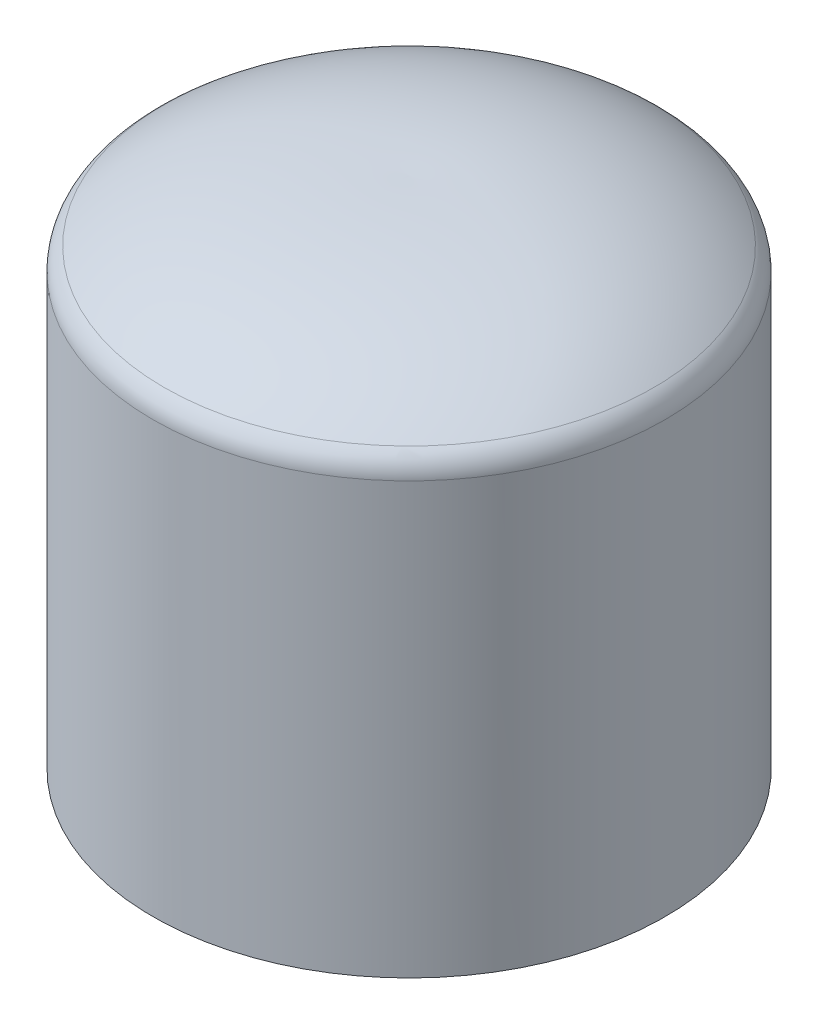
SolidWorks part; units mm, degrees
ref_plane "Front Plane" through (0, 0, 0) normal (0, 0, 1) x (1, 0, 0)
ref_plane "Top Plane" through (0, 0, 0) normal (0, 1, 0) x (1, 0, 0)
ref_plane "Right Plane" through (0, 0, 0) normal (1, 0, 0) x (0, 0, -1)
sketch "Sketch1" plane through (0, 0, 0) normal (1, 0, 0) x (0, 0, -1)
  line L0 (-10.7442, 22.4102) -> (-10.7442, 0)
  line L1 (0, 25.4751) -> (0, 27.94)
  line L2 (-13.9192, 24.13) -> (-13.9192, 0)
  line L3 (-13.9192, 0) -> (-10.7442, 0)
  line L4 (-10.343, 23.1158) -> (-10.343, 22.4102)
  line L5 (0, 0) -> (0, 36.7671) construction
  line L6 (-10.343, 22.4102) -> (-10.7442, 22.4102)
  spline S0 degree 3 poles (-13.9192, 24.13) (-10.0666, 27.4116) (-4.864, 28.0856) (0, 27.94) knots 0 0 0 0 1 1 1 1
  spline S1 degree 3 poles (-10.343, 23.1158) (-7.1333, 24.733) (-3.6857, 25.5194) (0, 25.4751) knots 0.040117 0.040117 0.040117 0.040117 1 1 1 1
  dimension "D1" = 10.7442
  dimension "D2" = 3.175
  dimension "D4" = 24.13
  dimension "D6" = 3.048
revolve "Revolve1" add sketch "Sketch1" angle 360 about L5
fillet "Fillet1" radius 0.508 1 edges at (0, 0, -10.7442)
fillet "Fillet2" radius 1.524 1 edges at (0, 24.13, -13.9192)
